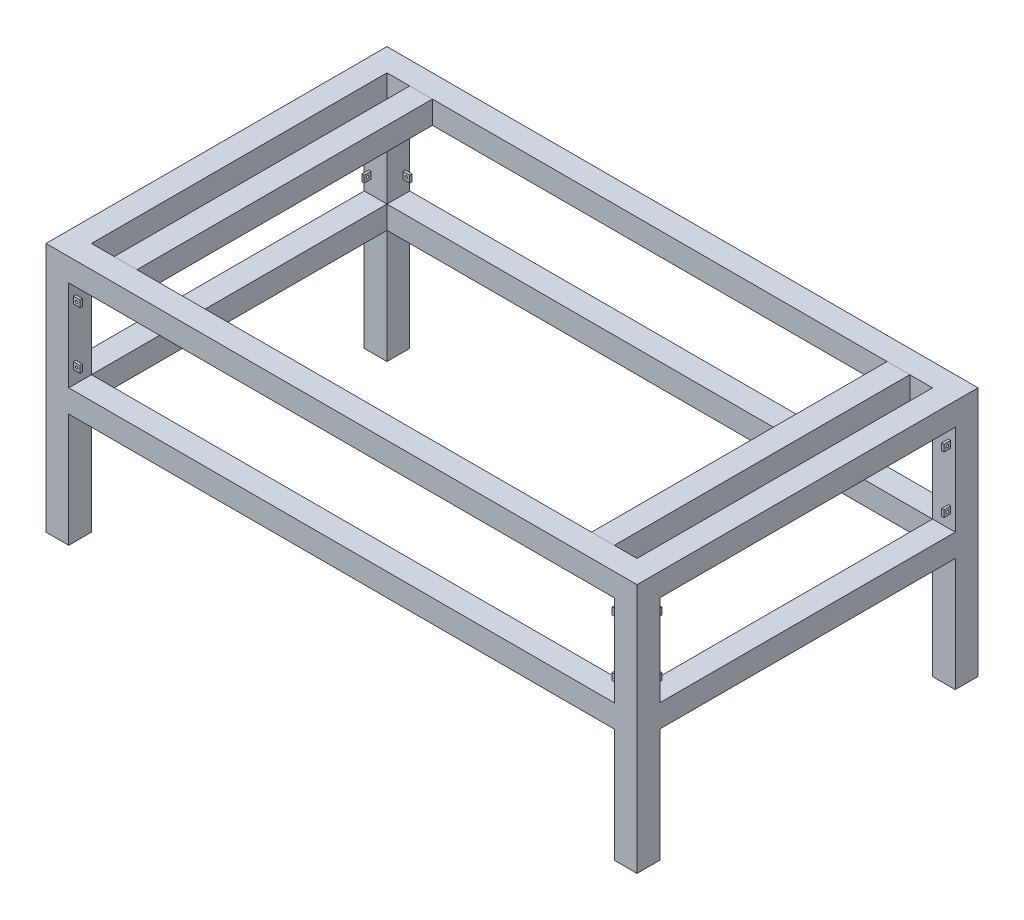
SolidWorks part; units mm, degrees
ref_plane "Plan de face" through (0, 0, 0) normal (0, 0, 1) x (1, 0, 0)
ref_plane "Plan de dessus" through (0, 0, 0) normal (0, 1, 0) x (1, 0, 0)
ref_plane "Plan de droite" through (0, 0, 0) normal (1, 0, 0) x (0, 0, -1)
sketch "Esquisse1" plane through (0, 0, 0) normal (0, 1, 0) x (1, 0, 0)
  line L1 (0, 0) -> (1300, 0)
  line L2 (0, 0) -> (0, 750)
  line L3 (0, 750) -> (1300, 750)
  line L4 (1300, 0) -> (1300, 750)
  line L5 (50, 700) -> (1250, 700)
  line L6 (50, 700) -> (50, 50)
  line L7 (50, 50) -> (1250, 50)
  line L8 (1250, 700) -> (1250, 50)
  dimension "D1" = 1300
  dimension "D2" = 750
  dimension "D3" = 50
  dimension "D4" = 50
  dimension "D5" = 50
  dimension "D6" = 50
extrude "Boss.-Extru.1" add sketch "Esquisse1" against normal blind 550
sketch "Esquisse2" plane through (0, 0, 0) normal (0, 0, 1) x (1, 0, 0)
  line L0 (0, 0) -> (1300, 0) construction
  line L1 (50, -50) -> (1250, -50)
  line L2 (50, -50) -> (50, -250)
  line L3 (50, -250) -> (1250, -250)
  line L4 (1250, -50) -> (1250, -250)
  line L5 (50, -300) -> (1250, -300)
  line L6 (50, -300) -> (50, -550)
  line L7 (50, -550) -> (1250, -550)
  line L8 (1250, -300) -> (1250, -550)
  line L9 (0, -550) -> (1300, -550) construction
  line L10 (1300, -550) -> (1300, 0) construction
  line L11 (0, -550) -> (0, 0) construction
  point P12 (1250, -425)
  dimension "D1" = 50
  dimension "D2" = 50
  dimension "D3" = 200
  dimension "D4" = 0
  dimension "D5" = 50
  dimension "D6" = 50
  dimension "D7" = 50
  dimension "D8" = 50
extrude "Enlèv. mat.-Extru.1" cut sketch "Esquisse2" against normal through all
sketch "Esquisse3" plane through (0, 0, 0) normal (-1, 0, 0) x (0, 0, 1)
  line L0 (-750, -550) -> (0, -550) construction
  line L1 (-700, -50) -> (-50, -50)
  line L2 (-700, -50) -> (-700, -250)
  line L3 (-700, -250) -> (-50, -250)
  line L4 (-50, -50) -> (-50, -250)
  line L5 (-700, -300) -> (-50, -300)
  line L6 (-700, -300) -> (-700, -550)
  line L7 (-700, -550) -> (-50, -550)
  line L8 (-50, -300) -> (-50, -550)
  line L9 (-750, 0) -> (0, 0) construction
  line L10 (0, -550) -> (0, 0) construction
  line L11 (-750, -550) -> (-750, 0) construction
  dimension "D1" = 50
  dimension "D2" = 50
  dimension "D3" = 50
  dimension "D4" = 50
  dimension "D5" = 50
  dimension "D6" = 200
  dimension "D7" = 50
extrude "Enlèv. mat.-Extru.2" cut sketch "Esquisse3" against normal through all
sketch "Esquisse4" plane through (0, 0, 0) normal (0, 1, 0) x (1, 0, 0)
  line L0 (1250, 700) -> (50, 700) construction
  line L1 (100, 700) -> (150, 700)
  line L2 (100, 700) -> (100, 50)
  line L3 (100, 50) -> (150, 50)
  line L4 (150, 700) -> (150, 50)
  line L5 (50, 50) -> (1250, 50) construction
  line L6 (50, 700) -> (50, 50) construction
  line L7 (1150, 700) -> (1200, 700)
  line L8 (1150, 700) -> (1150, 50)
  line L9 (1150, 50) -> (1200, 50)
  line L10 (1200, 700) -> (1200, 50)
  line L11 (1250, 50) -> (1250, 700) construction
  dimension "D1" = 50
  dimension "D2" = 50
  dimension "D3" = 50
  dimension "D4" = 50
extrude "Boss.-Extru.2" add sketch "Esquisse4" against normal blind 50 separate body
sketch "Esquisse5" plane through (1250, 0, 0) normal (-1, 0, 0) x (0, 0, 1)
  line L0 (-750, -250) -> (-750, -50) construction
  line L1 (-750, -80) -> (-735, -80)
  line L2 (-750, -80) -> (-750, -95)
  line L3 (-750, -95) -> (-735, -95)
  line L4 (-735, -80) -> (-735, -95)
  line L5 (-740, -80) -> (-740, -95)
  line L6 (-750, -205) -> (-735, -205)
  line L7 (-750, -205) -> (-750, -220)
  line L8 (-750, -220) -> (-735, -220)
  line L9 (-735, -205) -> (-735, -220)
  line L10 (-740, -205) -> (-740, -220)
  line L11 (-750, -50) -> (-700, -50) construction
  line L12 (-750, -250) -> (-700, -250) construction
  dimension "D1" = 10
  dimension "D2" = 5
  dimension "D3" = 5
  dimension "D4" = 15
  dimension "D5" = 15
  dimension "D6" = 30
  dimension "D7" = 30
extrude "Boss.-Extru.3" add sketch "Esquisse5" along normal blind 15 contours L1 L5 L3 L4 | L6 L10 L8 L9
sketch "Esquisse6" plane through (0, 0, -700) normal (0, 0, 1) x (1, 0, 0)
  line L0 (1300, -50) -> (1300, -250) construction
  line L1 (1300, -80) -> (1285, -80)
  line L2 (1300, -80) -> (1300, -95)
  line L3 (1300, -95) -> (1285, -95)
  line L4 (1285, -80) -> (1285, -95)
  line L5 (1290, -80) -> (1290, -95)
  line L6 (1300, -220) -> (1285, -220)
  line L7 (1300, -220) -> (1300, -205)
  line L8 (1300, -205) -> (1285, -205)
  line L9 (1285, -220) -> (1285, -205)
  line L10 (1290, -205) -> (1290, -220)
  line L11 (1300, -50) -> (1250, -50) construction
  line L12 (1300, -250) -> (1250, -250) construction
  point P18 (1292.5, -220)
  dimension "D1" = 15
  dimension "D2" = 15
  dimension "D3" = 5
  dimension "D4" = 5
  dimension "D5" = 10
  dimension "D6" = 30
  dimension "D7" = 30
extrude "Boss.-Extru.4" add sketch "Esquisse6" along normal blind 15 contours L5 L1 L4 L3 | L10 L8 L9 L6
sketch "Esquisse7" plane through (50, 0, 0) normal (1, 0, 0) x (0, 0, -1)
  line L0 (750, -50) -> (750, -250) construction
  line L1 (750, -80) -> (735, -80)
  line L2 (750, -80) -> (750, -95)
  line L3 (750, -95) -> (735, -95)
  line L4 (735, -80) -> (735, -95)
  line L5 (740, -80) -> (740, -95)
  line L6 (750, -220) -> (735, -220)
  line L7 (750, -220) -> (750, -205)
  line L8 (750, -205) -> (735, -205)
  line L9 (735, -220) -> (735, -205)
  line L10 (740, -205) -> (740, -220)
  line L11 (750, -250) -> (700, -250) construction
  line L12 (750, -50) -> (700, -50) construction
  dimension "D1" = 15
  dimension "D2" = 15
  dimension "D3" = 10
  dimension "D4" = 5
  dimension "D5" = 5
  dimension "D6" = 30
  dimension "D7" = 30
extrude "Boss.-Extru.5" add sketch "Esquisse7" along normal blind 15 contours L5 L1 L4 L3 | L10 L8 L9 L6
sketch "Esquisse8" plane through (0, 0, -700) normal (0, 0, 1) x (1, 0, 0)
  line L0 (0, -50) -> (0, -250) construction
  line L1 (10, -80) -> (10, -95)
  line L2 (0, -80) -> (15, -80)
  line L3 (0, -80) -> (0, -95)
  line L4 (0, -95) -> (15, -95)
  line L5 (15, -80) -> (15, -95)
  line L6 (0, -205) -> (15, -205)
  line L7 (0, -205) -> (0, -220)
  line L8 (0, -220) -> (15, -220)
  line L9 (15, -205) -> (15, -220)
  line L10 (10, -205) -> (10, -220)
  line L11 (50, -250) -> (0, -250) construction
  line L13 (50, -50) -> (0, -50) construction
  point P16 (7.5, -220)
  dimension "D1" = 15
  dimension "D2" = 5
  dimension "D3" = 10
  dimension "D4" = 30
  dimension "D5" = 5
  dimension "D6" = 10
  dimension "D7" = 15
  dimension "D8" = 30
extrude "Boss.-Extru.6" add sketch "Esquisse8" along normal blind 15 contours L5 L2 L1 L4 | L6 L10 L8 L9
sketch "Esquisse10" plane through (50, 0, 0) normal (1, 0, 0) x (0, 0, -1)
  line L0 (0, -50) -> (0, -250) construction
  line L1 (0, -80) -> (15, -80)
  line L2 (0, -80) -> (0, -95)
  line L3 (0, -95) -> (15, -95)
  line L4 (15, -80) -> (15, -95)
  line L5 (10, -80) -> (10, -95)
  line L6 (0, -205) -> (15, -205)
  line L7 (0, -205) -> (0, -220)
  line L8 (0, -220) -> (15, -220)
  line L9 (15, -205) -> (15, -220)
  line L10 (10, -205) -> (10, -220)
  line L11 (50, -250) -> (0, -250) construction
  line L12 (50, -50) -> (0, -50) construction
  point P18 (7.5, -80)
  dimension "D1" = 5
  dimension "D2" = 5
  dimension "D3" = 15
  dimension "D4" = 15
  dimension "D5" = 15
  dimension "D6" = 15
  dimension "D7" = 30
  dimension "D8" = 30
extrude "Boss.-Extru.7" add sketch "Esquisse10" along normal blind 15 contours L1 L5 L3 L4 | L6 L10 L8 L9
sketch "Esquisse12" plane through (0, 0, -50) normal (0, 0, -1) x (-1, 0, 0)
  line L0 (0, -250) -> (0, -50) construction
  line L1 (0, -80) -> (-15, -80)
  line L2 (0, -80) -> (0, -95)
  line L3 (0, -95) -> (-15, -95)
  line L4 (-15, -80) -> (-15, -95)
  line L5 (-10, -80) -> (-10, -95)
  line L6 (0, -205) -> (-15, -205)
  line L7 (0, -205) -> (0, -220)
  line L8 (0, -220) -> (-15, -220)
  line L9 (-15, -205) -> (-15, -220)
  line L10 (-10, -205) -> (-10, -220)
  line L11 (-50, -50) -> (0, -50) construction
  line L12 (-50, -250) -> (0, -250) construction
  point P14 (-15, -87.5)
  dimension "D1" = 15
  dimension "D2" = 15
  dimension "D3" = 15
  dimension "D4" = 15
  dimension "D5" = 5
  dimension "D6" = 5
  dimension "D7" = 30
  dimension "D8" = 30
extrude "Boss.-Extru.8" add sketch "Esquisse12" along normal blind 15 contours L5 L1 L4 L3 | L10 L6 L9 L8
sketch "Esquisse14" plane through (1250, 0, 0) normal (-1, 0, 0) x (0, 0, 1)
  line L0 (0, -250) -> (0, -50) construction
  line L1 (0, -80) -> (-15, -80)
  line L2 (0, -80) -> (0, -95)
  line L3 (0, -95) -> (-15, -95)
  line L4 (-15, -80) -> (-15, -95)
  line L5 (-10, -80) -> (-10, -95)
  line L6 (0, -205) -> (-15, -205)
  line L7 (0, -205) -> (0, -220)
  line L8 (0, -220) -> (-15, -220)
  line L9 (-15, -205) -> (-15, -220)
  line L10 (-10, -205) -> (-10, -220)
  line L11 (-50, -250) -> (0, -250) construction
  line L12 (-50, -50) -> (0, -50) construction
  point P18 (-15, -87.5)
  dimension "D1" = 15
  dimension "D2" = 5
  dimension "D3" = 15
  dimension "D4" = 30
  dimension "D5" = 30
  dimension "D6" = 5
  dimension "D7" = 15
  dimension "D8" = 15
extrude "Boss.-Extru.9" add sketch "Esquisse14" along normal blind 15 contours L5 L1 L4 L3 | L10 L6 L9 L8
sketch "Esquisse15" plane through (0, 0, -50) normal (0, 0, -1) x (-1, 0, 0)
  line L0 (-1300, -250) -> (-1300, -50) construction
  line L1 (-1300, -80) -> (-1285, -80)
  line L2 (-1300, -80) -> (-1300, -95)
  line L3 (-1300, -95) -> (-1285, -95)
  line L4 (-1285, -80) -> (-1285, -95)
  line L5 (-1290, -80) -> (-1290, -95)
  line L6 (-1300, -205) -> (-1285, -205)
  line L7 (-1300, -205) -> (-1300, -220)
  line L8 (-1300, -220) -> (-1285, -220)
  line L9 (-1285, -205) -> (-1285, -220)
  line L10 (-1290, -205) -> (-1290, -220)
  line L11 (-1300, -50) -> (-1250, -50) construction
  line L12 (-1300, -250) -> (-1250, -250) construction
  point P14 (-1285, -212.5)
  point P15 (-1300, -212.5)
  dimension "D1" = 15
  dimension "D2" = 15
  dimension "D3" = 15
  dimension "D4" = 5
  dimension "D5" = 15
  dimension "D6" = 30
  dimension "D7" = 30
extrude "Boss.-Extru.10" add sketch "Esquisse15" along normal blind 15 contours L6 L10 L8 L9 | L1 L5 L3 L4
sketch "Esquisse16" plane through (1290, 0, 0) normal (1, 0, 0) x (0, 0, -1)
  line L0 (65, -95) -> (50, -95) construction
  line L1 (65, -80) -> (50, -80) construction
  line L2 (65, -80) -> (65, -95) construction
  line L3 (50, -80) -> (50, -95) construction
  line L4 (65, -205) -> (65, -220) construction
  line L5 (65, -220) -> (50, -220) construction
  line L6 (685, -80) -> (685, -95) construction
  line L7 (685, -80) -> (700, -80) construction
  line L8 (685, -205) -> (685, -220) construction
  line L9 (685, -205) -> (700, -205) construction
  circle A0 centre (57.5, -87.5) radius 2.75
  circle A1 centre (57.5, -212.5) radius 2.75
  circle A2 centre (692.5, -87.5) radius 2.75
  circle A3 centre (692.5, -212.5) radius 2.75
  dimension "D5" = 5.5
  dimension "D6" = 5.5
  dimension "D9" = 5.5
  dimension "D12" = 5.5
  dimension "D1" = 15
  dimension "D2" = 7.5
  dimension "D3" = 15
  dimension "D4" = 7.5
  dimension "D7" = 7.5
  dimension "D8" = 7.5
  dimension "D10" = 7.5
  dimension "D11" = 7.5
  dimension "D13" = 7.5
  dimension "D14" = 7.5
extrude "Enlèv. mat.-Extru.3" cut sketch "Esquisse16" against normal blind 1500
sketch "Esquisse17" plane through (0, 0, -10) normal (0, 0, 1) x (1, 0, 0)
  line L0 (65, -205) -> (50, -205) construction
  line L1 (65, -205) -> (65, -220) construction
  line L2 (65, -80) -> (50, -80) construction
  line L3 (65, -80) -> (65, -95) construction
  line L4 (1235, -80) -> (1235, -95) construction
  line L5 (1235, -95) -> (1250, -95) construction
  line L6 (1235, -205) -> (1250, -205) construction
  line L8 (1235, -205) -> (1235, -220) construction
  circle A0 centre (57.5, -87.5) radius 2.75
  circle A1 centre (57.5, -212.5) radius 2.75
  circle A2 centre (1242.5, -212.5) radius 2.75
  circle A3 centre (1242.5, -87.5) radius 2.75
  point P24 (1235, -210.758)
  dimension "D1" = 5.5
  dimension "D2" = 5.5
  dimension "D3" = 5.5
  dimension "D4" = 5.5
  dimension "D5" = 7.5
  dimension "D6" = 7.5
  dimension "D7" = 7.5
  dimension "D8" = 7.5
  dimension "D9" = 7.5
  dimension "D10" = 7.5
  dimension "D11" = 7.5
  dimension "D12" = 7.5
extrude "Enlèv. mat.-Extru.4" cut sketch "Esquisse17" against normal blind 1000
